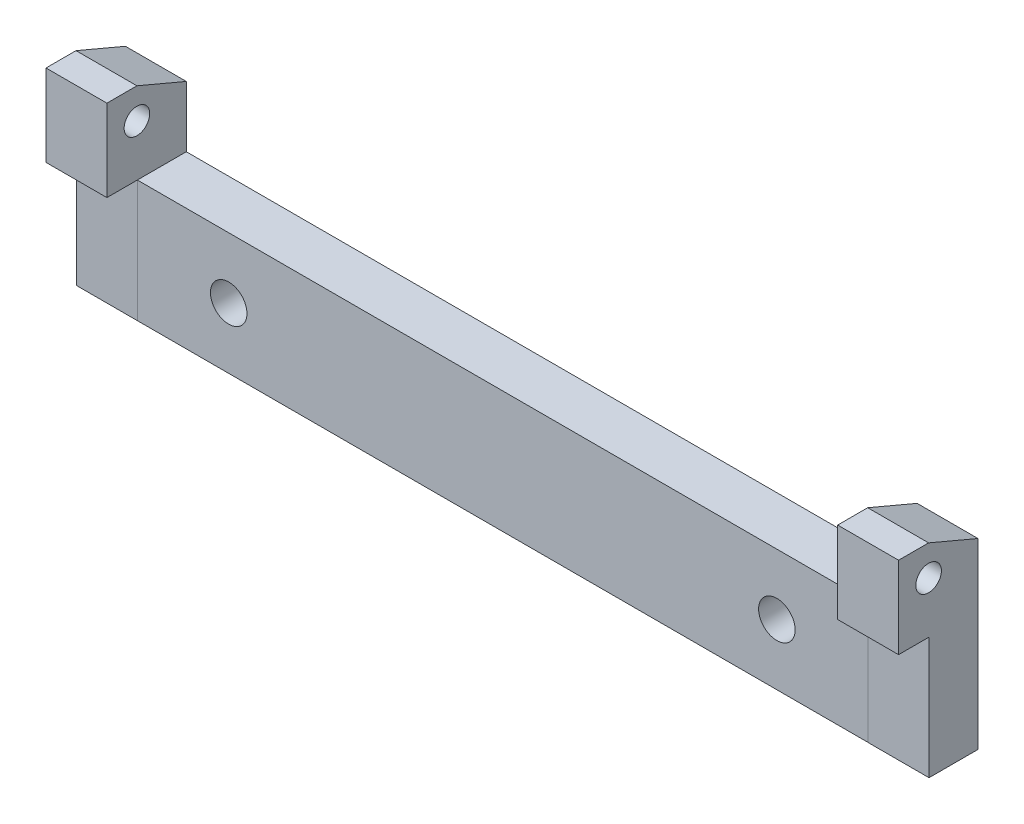
SolidWorks part; units mm, degrees
ref_plane "Спереди" through (0, 0, 0) normal (0, 0, 1) x (1, 0, 0)
ref_plane "Сверху" through (0, 0, 0) normal (0, 1, 0) x (1, 0, 0)
ref_plane "Справа" through (0, 0, 0) normal (1, 0, 0) x (0, 0, -1)
ref_plane "Плоскость4" through (120, 0, 0) normal (1, 0, 0) x (0, 0, -1)
sketch "Эскиз1" plane through (120, 0, 0) normal (1, 0, 0) x (0, 0, -1)
  line L1 (27.8889, 13.434) -> (36, 10)
  line L2 (36, 10) -> (36, 0) construction
  line L3 (52, 10) -> (36, 10) construction
  line L4 (36, 10) -> (36, -20)
  line L5 (36, -20) -> (27.9583, -20)
  line L6 (27.9583, -20) -> (27.9583, 0)
  line L7 (0, 0) -> (36, 0) construction
  line L8 (27.9583, 0) -> (22.9583, 0)
  line L9 (-28.6, 0) -> (28.6, 0) construction
  line L10 (22.9583, 0) -> (22.9583, 13.434)
  line L11 (22.9583, 13.434) -> (27.8889, 13.434)
  circle A0 centre (27.8889, 8.434) radius 2.1
extrude "Бобышка-Вытянуть1" add sketch "Эскиз1" along normal blind 10
ref_plane "Плоскость5" through (0, 0, 0) normal (-1, 0, 0) x (0, 0, 1)
sketch "Эскиз2" plane through (0, 0, 0) normal (-1, 0, 0) x (0, 0, 1)
  line L0 (-22.9583, 13.434) -> (-27.8889, 13.434)
  line L1 (-27.8889, 13.434) -> (-36, 10)
  line L2 (-36, 10) -> (-36, -20)
  line L3 (-36, -20) -> (-27.9583, -20)
  line L4 (-27.9583, -20) -> (-27.9583, 0)
  line L5 (-27.9583, 0) -> (-22.9583, 0)
  line L6 (-22.9583, 0) -> (-22.9583, 13.434)
  circle A0 centre (-27.8889, 8.434) radius 2.1
extrude "Бобышка-Вытянуть2" add sketch "Эскиз2" along normal blind 10 separate body
ref_plane "Плоскость6" through (0, 0, 0) normal (0, -1, 0) x (-1, 0, 0)
sketch "Эскиз3" plane through (0, 0, 0) normal (0, -1, 0) x (-1, 0, 0)
  line L7 (-120, 27.9757) -> (0, 27.9583)
  line L8 (-120, 28.6) -> (-120, -28.6) construction
  line L9 (0, -28.6) -> (0, 28.6) construction
  line L10 (10, 27.9583) -> (0, 27.9583) construction
  line L11 (0, 27.9583) -> (0, 36)
  line L12 (10, 36) -> (0, 36) construction
  line L13 (0, 36) -> (-120, 36)
  line L14 (-120, 36) -> (-120, 27.9757)
extrude "Бобышка-Вытянуть3" add sketch "Эскиз3" along normal blind 20
ref_plane "Плоскость7" through (-0.0041, 0, -27.9583) normal (0.0001, 0, 1) x (1, 0, -0.0001)
sketch "Эскиз4" plane through (-0.0041, 0, -27.9583) normal (0.0001, 0, 1) x (1, 0, -0.0001)
  circle A0 centre (15.0041, -10) radius 3
  circle A1 centre (105.0041, -10) radius 3
extrude "Вырез-Вытянуть1" cut sketch "Эскиз4" against normal blind 20
